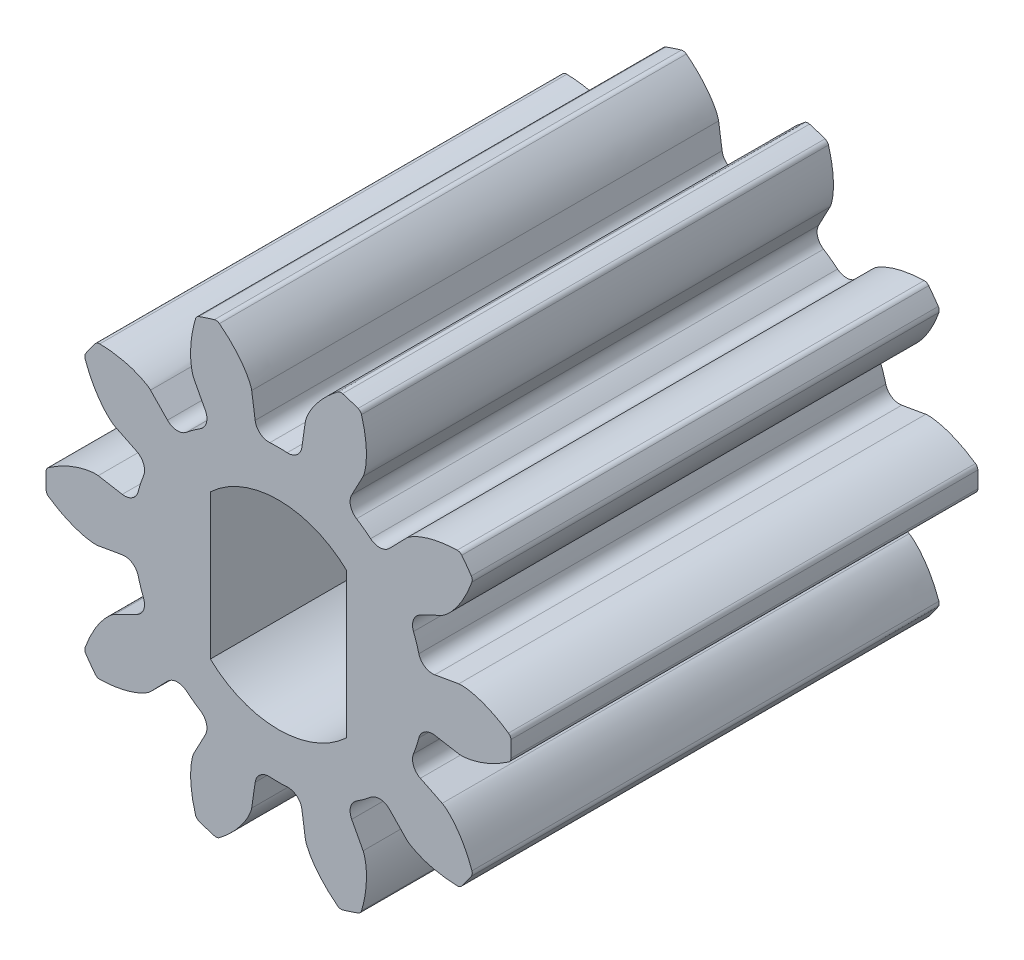
SolidWorks part; units mm, degrees
material "ABS"
ref_plane "Front" through (0, 0, 0) normal (0, 0, 1) x (1, 0, 0)
ref_plane "Top" through (0, 0, 0) normal (0, 1, 0) x (1, 0, 0)
ref_plane "Right" through (0, 0, 0) normal (1, 0, 0) x (0, 0, -1)
sketch "Sketch1" plane through (0, 0, 0) normal (0, 0, 1) x (1, 0, 0)
  circle A0 centre (0, 0) radius 6.35
extrude "Boss-Extrude1" add sketch "Sketch1" along normal blind 12.7
sketch "Sketch3" plane through (0, 0, 0) normal (0, 0, 1) x (1, 0, 0)
  line L0 (0, 0) -> (43.7181, 0) construction
  line L2 (0, 0) -> (-0.5624, 3.9287) construction
  line L3 (0, 0) -> (0.5624, 3.9287) construction
  line L4 (0.5624, 3.9287) -> (0.7046, 4.9224) construction
  line L5 (0, 0) -> (0, 61.276) construction
  line L6 (-0.5624, 3.9287) -> (-0.7046, 4.9224) construction
  circle A0 centre (0, 0) radius 6.35 construction
  circle A1 centre (0, 0) radius 5.2917 construction
  circle A2 centre (0, 0) radius 4.9725 construction
  arc A3 (0.5624, 3.9287) -> (-0.5624, 3.9287) centre (0, 0) ccw construction
  arc A5 (1.6642, 6.128) -> (-1.6642, 6.128) centre (0, 0) ccw
  spline S0 degree 4 poles (-0.7046, 4.9224) (-0.705, 4.9247) (-0.7061, 4.9311) (-0.7087, 4.9431) (-0.7137, 4.9626) (-0.721, 4.9872) (-0.7316, 5.0187) (-0.7454, 5.0554) (-0.7621, 5.0953) (-0.7818, 5.1381) (-0.8028, 5.1804) (-0.825, 5.2221) (-0.8483, 5.2631) (-0.8779, 5.3122) (-0.9151, 5.3703) (-0.9613, 5.437) (-1.0167, 5.511) (-1.0764, 5.5846) (-1.1378, 5.6556) (-1.2027, 5.7255) (-1.2676, 5.7919) (-1.338, 5.8588) (-1.4044, 5.9196) (-1.4819, 5.9855) (-1.5453, 6.0379) (-1.6323, 6.1046) (-1.6846, 6.1433) (-1.7469, 6.1876) (-1.7752, 6.2068) (-1.7925, 6.2186) knots 0 0 0 0 0 0.005377 0.015084 0.028532 0.04661 0.064855 0.092111 0.119476 0.146842 0.174209 0.201575 0.228941 0.256307 0.307035 0.361767 0.4165 0.471232 0.525964 0.580697 0.635429 0.690161 0.744894 0.799626 0.854358 0.909091 0.954545 1 1 1 1 1 construction
  spline S1 degree 4 poles (-0.7046, 4.9224) (-0.705, 4.9247) (-0.7061, 4.9311) (-0.7087, 4.9431) (-0.7137, 4.9626) (-0.721, 4.9872) (-0.7316, 5.0187) (-0.7454, 5.0554) (-0.7621, 5.0953) (-0.7818, 5.1381) (-0.8028, 5.1804) (-0.825, 5.2221) (-0.8483, 5.2631) (-0.8779, 5.3122) (-0.9151, 5.3703) (-0.9613, 5.437) (-1.0167, 5.511) (-1.0764, 5.5846) (-1.1378, 5.6556) (-1.2027, 5.7255) (-1.2676, 5.7919) (-1.338, 5.8588) (-1.4044, 5.9196) (-1.4819, 5.9855) (-1.5453, 6.0379) (-1.6134, 6.0902) (-1.647, 6.1153) (-1.6642, 6.128) knots 0 0 0 0 0 0.005377 0.015084 0.028532 0.04661 0.064855 0.092111 0.119476 0.146842 0.174209 0.201575 0.228941 0.256307 0.307035 0.361767 0.4165 0.471232 0.525964 0.580697 0.635429 0.690161 0.744894 0.799626 0.854358 0.909091 0.909091 0.909091 0.909091 0.909091
  spline S2 degree 4 poles (0.7046, 4.9224) (0.705, 4.9247) (0.7061, 4.9311) (0.7087, 4.9431) (0.7137, 4.9626) (0.721, 4.9872) (0.7316, 5.0187) (0.7454, 5.0554) (0.7621, 5.0953) (0.7818, 5.1381) (0.8028, 5.1804) (0.825, 5.2221) (0.8483, 5.2631) (0.8779, 5.3122) (0.9151, 5.3703) (0.9613, 5.437) (1.0167, 5.511) (1.0764, 5.5846) (1.1378, 5.6556) (1.2027, 5.7255) (1.2676, 5.7919) (1.338, 5.8588) (1.4044, 5.9196) (1.4819, 5.9855) (1.5453, 6.0379) (1.6323, 6.1046) (1.6846, 6.1433) (1.7469, 6.1876) (1.7752, 6.2068) (1.7925, 6.2186) knots 0 0 0 0 0 0.005377 0.015084 0.028532 0.04661 0.064855 0.092111 0.119476 0.146842 0.174209 0.201575 0.228941 0.256307 0.307035 0.361767 0.4165 0.471232 0.525964 0.580697 0.635429 0.690161 0.744894 0.799626 0.854358 0.909091 0.954545 1 1 1 1 1 construction
  spline S3 degree 4 poles (0.7046, 4.9224) (0.705, 4.9247) (0.7061, 4.9311) (0.7087, 4.9431) (0.7137, 4.9626) (0.721, 4.9872) (0.7316, 5.0187) (0.7454, 5.0554) (0.7621, 5.0953) (0.7818, 5.1381) (0.8028, 5.1804) (0.825, 5.2221) (0.8483, 5.2631) (0.8779, 5.3122) (0.9151, 5.3703) (0.9613, 5.437) (1.0167, 5.511) (1.0764, 5.5846) (1.1378, 5.6556) (1.2027, 5.7255) (1.2676, 5.7919) (1.338, 5.8588) (1.4044, 5.9196) (1.4819, 5.9855) (1.5453, 6.0379) (1.6134, 6.0902) (1.647, 6.1153) (1.6642, 6.128) knots 0 0 0 0 0 0.005377 0.015084 0.028532 0.04661 0.064855 0.092111 0.119476 0.146842 0.174209 0.201575 0.228941 0.256307 0.307035 0.361767 0.4165 0.471232 0.525964 0.580697 0.635429 0.690161 0.744894 0.799626 0.854358 0.909091 0.909091 0.909091 0.909091 0.909091
  point P0 (0, 3.9688)
sketch "DCLTBC" plane through (0, 0, 0) normal (0, 0, 1) x (1, 0, 0)
  line L0 (0, 0) -> (41.04, 0) construction
  line L1 (-0.5624, 3.9287) -> (-0.7046, 4.9224) construction
  line L2 (0.5624, 3.9287) -> (0.7046, 4.9224) construction
  line L3 (-0.5624, 3.9287) -> (-0.7046, 4.9224)
  line L4 (0.5624, 3.9287) -> (0.7046, 4.9224)
  line L5 (0, 0) -> (0, 104.9356) construction
  circle A0 centre (0, 0) radius 6.35
  circle A1 centre (0, 0) radius 5.2917 construction
  circle A2 centre (0, 0) radius 4.9725 construction
  arc A3 (0.5624, 3.9287) -> (-0.5624, 3.9287) centre (0, 0) ccw construction
  arc A4 (0.5624, 3.9287) -> (-0.5624, 3.9287) centre (0, 0) ccw
  spline S0 degree 4 poles (-988.7588, -149.038) (-11.8151, 2.4708) (-0.7866, 4.3496) (-0.6413, 4.6789) (-0.7137, 4.9626) (-0.721, 4.9872) (-0.7316, 5.0187) (-0.7454, 5.0554) (-0.7621, 5.0953) (-0.7818, 5.1381) (-0.8028, 5.1804) (-0.825, 5.2221) (-0.8483, 5.2631) (-0.8779, 5.3122) (-0.9151, 5.3703) (-0.9613, 5.437) (-1.0167, 5.511) (-1.0764, 5.5846) (-1.1378, 5.6556) (-1.2027, 5.7255) (-1.2676, 5.7919) (-1.338, 5.8588) (-1.4044, 5.9196) (-1.4819, 5.9855) (-1.8387, 6.2805) (-3.231, 7.2231) (17.05, -7.85) (-807.2758, 598.5552) knots -0.632257 -0.632257 -0.632257 -0.632257 -0.632257 0.005377 0.015084 0.028532 0.04661 0.064855 0.092111 0.119476 0.146842 0.174209 0.201575 0.228941 0.256307 0.307035 0.361767 0.4165 0.471232 0.525964 0.580697 0.635429 0.690161 0.744894 0.799626 0.854358 1.920904 1.920904 1.920904 1.920904 1.920904 only from (-0.7046, 4.9224) to (-1.6642, 6.128) construction
  spline S1 degree 4 poles (988.7588, -149.038) (11.8151, 2.4708) (0.7866, 4.3496) (0.6413, 4.6789) (0.7137, 4.9626) (0.721, 4.9872) (0.7316, 5.0187) (0.7454, 5.0554) (0.7621, 5.0953) (0.7818, 5.1381) (0.8028, 5.1804) (0.825, 5.2221) (0.8483, 5.2631) (0.8779, 5.3122) (0.9151, 5.3703) (0.9613, 5.437) (1.0167, 5.511) (1.0764, 5.5846) (1.1378, 5.6556) (1.2027, 5.7255) (1.2676, 5.7919) (1.338, 5.8588) (1.4044, 5.9196) (1.4819, 5.9855) (1.8387, 6.2805) (3.231, 7.2231) (-17.05, -7.85) (807.2758, 598.5552) knots -0.632257 -0.632257 -0.632257 -0.632257 -0.632257 0.005377 0.015084 0.028532 0.04661 0.064855 0.092111 0.119476 0.146842 0.174209 0.201575 0.228941 0.256307 0.307035 0.361767 0.4165 0.471232 0.525964 0.580697 0.635429 0.690161 0.744894 0.799626 0.854358 1.920904 1.920904 1.920904 1.920904 1.920904 only from (0.7046, 4.9224) to (1.6642, 6.128) construction
  spline S2 degree 4 poles (-0.7046, 4.9224) (-0.705, 4.9247) (-0.7061, 4.9311) (-0.7087, 4.9431) (-0.7137, 4.9626) (-0.721, 4.9872) (-0.7316, 5.0187) (-0.7454, 5.0554) (-0.7621, 5.0953) (-0.7818, 5.1381) (-0.8028, 5.1804) (-0.825, 5.2221) (-0.8483, 5.2631) (-0.8779, 5.3122) (-0.9151, 5.3703) (-0.9613, 5.437) (-1.0167, 5.511) (-1.0764, 5.5846) (-1.1378, 5.6556) (-1.2027, 5.7255) (-1.2676, 5.7919) (-1.338, 5.8588) (-1.4044, 5.9196) (-1.4819, 5.9855) (-1.5453, 6.0379) (-1.6134, 6.0902) (-1.647, 6.1153) (-1.6642, 6.128) knots 0 0 0 0 0 0.005377 0.015084 0.028532 0.04661 0.064855 0.092111 0.119476 0.146842 0.174209 0.201575 0.228941 0.256307 0.307035 0.361767 0.4165 0.471232 0.525964 0.580697 0.635429 0.690161 0.744894 0.799626 0.854358 0.909091 0.909091 0.909091 0.909091 0.909091
  spline S3 degree 4 poles (0.7046, 4.9224) (0.705, 4.9247) (0.7061, 4.9311) (0.7087, 4.9431) (0.7137, 4.9626) (0.721, 4.9872) (0.7316, 5.0187) (0.7454, 5.0554) (0.7621, 5.0953) (0.7818, 5.1381) (0.8028, 5.1804) (0.825, 5.2221) (0.8483, 5.2631) (0.8779, 5.3122) (0.9151, 5.3703) (0.9613, 5.437) (1.0167, 5.511) (1.0764, 5.5846) (1.1378, 5.6556) (1.2027, 5.7255) (1.2676, 5.7919) (1.338, 5.8588) (1.4044, 5.9196) (1.4819, 5.9855) (1.5453, 6.0379) (1.6134, 6.0902) (1.647, 6.1153) (1.6642, 6.128) knots 0 0 0 0 0 0.005377 0.015084 0.028532 0.04661 0.064855 0.092111 0.119476 0.146842 0.174209 0.201575 0.228941 0.256307 0.307035 0.361767 0.4165 0.471232 0.525964 0.580697 0.635429 0.690161 0.744894 0.799626 0.854358 0.909091 0.909091 0.909091 0.909091 0.909091
extrude "Cut-Extrude-DCLTBC" cut sketch "DCLTBC" along normal through all
fillet "Fillet-Tip-DCLTBC" radius 0.1775 2 edges at (1.6642, 6.128, 6.35) (-1.6642, 6.128, 6.35)
fillet "Fillet-Root-DCLTBC" radius 0.3551 2 edges at (-0.5624, 3.9287, 6.35) (0.5624, 3.9287, 6.35)
pattern_circular "CirPattern-DCLTBC" count 10 over 360 about axis through (0, 0, 12.7) along (0, 0, 1) of "Cut-Extrude-DCLTBC", "Fillet-Tip-DCLTBC", "Fillet-Root-DCLTBC"
sketch "DCGTBC" [suppressed] plane through (0, 0, 0) normal (0, 0, 1) x (1, 0, 0)
  line L0 (0, 0) -> (41.04, 0) construction
  line L1 (-22.6634, 1.9828) -> (0, 0) construction
  line L2 (0, 0) -> (22.6634, 1.9828) construction
  line L3 (0, 0) -> (-16.5124, 0)
  line L5 (0, 0) -> (0, 104.9356) construction
  circle A0 centre (0, 0) radius 25
  circle A1 centre (0, 0) radius 24 construction
  circle A2 centre (0, 0) radius 21.7514 construction
  arc A3 (0.0626, 22.7499) -> (-0.0626, 22.7499) centre (0, 0) ccw construction
  arc A11 (22.6634, 1.9828) -> (-22.6634, 1.9828) centre (0, 0) ccw
  spline S4 degree 4 poles (999.7589, -2.0808) (12.8658, 20.0937) (0.2547, 20.6746) (0.0189, 21.2606) (0.0654, 21.8429) (0.0715, 21.8997) (0.0812, 21.973) (0.095, 22.0592) (0.1126, 22.1539) (0.1343, 22.2566) (0.1583, 22.3589) (0.1845, 22.4607) (0.2124, 22.562) (0.2486, 22.6844) (0.2952, 22.8308) (0.3543, 23.0013) (0.4268, 23.1939) (0.5065, 23.3893) (0.5897, 23.5809) (0.6793, 23.7735) (0.7698, 23.9592) (0.8695, 24.151) (0.9643, 24.3275) (1.0767, 24.524) (1.517, 25.277) (3.0654, 27.5692) (-13.787, 0.9944) (540.7091, 867.0187) knots -0.561807 -0.561807 -0.561807 -0.561807 -0.561807 0.005377 0.015084 0.028532 0.04661 0.064855 0.092111 0.119476 0.146842 0.174209 0.201575 0.228941 0.256307 0.307035 0.361767 0.4165 0.471232 0.525964 0.580697 0.635429 0.690161 0.744894 0.799626 0.854358 1.731906 1.731906 1.731906 1.731906 1.731906 only from (0.0598, 21.7513) to (1.3455, 24.9638) construction
  spline S5 degree 4 poles (-999.7589, -2.0808) (-12.8658, 20.0937) (-0.2547, 20.6746) (-0.0189, 21.2606) (-0.0654, 21.8429) (-0.0715, 21.8997) (-0.0812, 21.973) (-0.095, 22.0592) (-0.1126, 22.1539) (-0.1343, 22.2566) (-0.1583, 22.3589) (-0.1845, 22.4607) (-0.2124, 22.562) (-0.2486, 22.6844) (-0.2952, 22.8308) (-0.3543, 23.0013) (-0.4268, 23.1939) (-0.5065, 23.3893) (-0.5897, 23.5809) (-0.6793, 23.7735) (-0.7698, 23.9592) (-0.8695, 24.151) (-0.9643, 24.3275) (-1.0767, 24.524) (-1.517, 25.277) (-3.0654, 27.5692) (13.787, 0.9944) (-540.7091, 867.0187) knots -0.561807 -0.561807 -0.561807 -0.561807 -0.561807 0.005377 0.015084 0.028532 0.04661 0.064855 0.092111 0.119476 0.146842 0.174209 0.201575 0.228941 0.256307 0.307035 0.361767 0.4165 0.471232 0.525964 0.580697 0.635429 0.690161 0.744894 0.799626 0.854358 1.731906 1.731906 1.731906 1.731906 1.731906 only from (-0.0598, 21.7513) to (-1.3455, 24.9638) construction
  spline S6 degree 4 poles (0.0598, 21.7513) (0.0599, 21.7565) (0.0603, 21.7709) (0.0618, 21.7983) (0.0654, 21.8429) (0.0715, 21.8997) (0.0812, 21.973) (0.095, 22.0592) (0.1126, 22.1539) (0.1343, 22.2566) (0.1583, 22.3589) (0.1845, 22.4607) (0.2124, 22.562) (0.2486, 22.6844) (0.2952, 22.8308) (0.3543, 23.0013) (0.4268, 23.1939) (0.5065, 23.3893) (0.5897, 23.5809) (0.6793, 23.7735) (0.7698, 23.9592) (0.8695, 24.151) (0.9643, 24.3275) (1.0767, 24.524) (1.1693, 24.6823) (1.27, 24.8447) (1.3197, 24.9235) (1.3455, 24.9638) knots 0 0 0 0 0 0.005377 0.015084 0.028532 0.04661 0.064855 0.092111 0.119476 0.146842 0.174209 0.201575 0.228941 0.256307 0.307035 0.361767 0.4165 0.471232 0.525964 0.580697 0.635429 0.690161 0.744894 0.799626 0.854358 0.909091 0.909091 0.909091 0.909091 0.909091
  spline S7 degree 4 poles (-0.0598, 21.7513) (-0.0599, 21.7565) (-0.0603, 21.7709) (-0.0618, 21.7983) (-0.0654, 21.8429) (-0.0715, 21.8997) (-0.0812, 21.973) (-0.095, 22.0592) (-0.1126, 22.1539) (-0.1343, 22.2566) (-0.1583, 22.3589) (-0.1845, 22.4607) (-0.2124, 22.562) (-0.2486, 22.6844) (-0.2952, 22.8308) (-0.3543, 23.0013) (-0.4268, 23.1939) (-0.5065, 23.3893) (-0.5897, 23.5809) (-0.6793, 23.7735) (-0.7698, 23.9592) (-0.8695, 24.151) (-0.9643, 24.3275) (-1.0767, 24.524) (-1.1693, 24.6823) (-1.27, 24.8447) (-1.3197, 24.9235) (-1.3455, 24.9638) knots 0 0 0 0 0 0.005377 0.015084 0.028532 0.04661 0.064855 0.092111 0.119476 0.146842 0.174209 0.201575 0.228941 0.256307 0.307035 0.361767 0.4165 0.471232 0.525964 0.580697 0.635429 0.690161 0.744894 0.799626 0.854358 0.909091 0.909091 0.909091 0.909091 0.909091
  dimension "D1" = 5
  dimension "D2" = 5
extrude "Cut-Extrude-DCGTBC" [suppressed] cut sketch "DCGTBC" along normal through all
fillet "Fillet-Tip-DCGTBC" [suppressed] radius 0.1775
pattern_circular "CirPattern-DCGTBC" [suppressed] count 10 over 360
sketch "Sketch4" plane through (0, 0, 12.7) normal (0, 0, 1) x (1, 0, 0)
  circle A1 centre (0, 0) radius 2.7051
  dimension "D1" = 5.4102
extrude "Cut-Extrude2" cut sketch "Sketch4" against normal through all
sketch "Sketch5" plane through (0, 0, 12.7) normal (0, 0, 1) x (1, 0, 0)
  line L0 (-1.8542, 1.9696) -> (-1.8542, -1.9696)
  line L1 (1.8542, 1.9696) -> (1.8542, -1.9696)
  circle A0 centre (0, 0) radius 2.7051 construction
  circle A1 centre (0, 0) radius 2.7051
  dimension "D1" = 3.7084
extrude "Boss-Extrude2" add sketch "Sketch5" against normal through all contours L0 A1 | L1 A1
sketch "Sketch6" plane through (0, 0, 0) normal (0, 0, -1) x (-1, 0, 0)
  line L4 (-1.9655, 2.0878) -> (-1.9655, -2.0878)
  line L5 (1.9655, -2.0878) -> (1.9655, 2.0878)
  arc A4 (-1.9655, -2.0878) -> (1.9655, -2.0878) centre (0, 0) ccw
  arc A5 (1.9655, 2.0878) -> (-1.9655, 2.0878) centre (0, 0) ccw
extrude "Boss-Extrude3" add sketch "Sketch6" against normal blind 3.175
sketch "Sketch8" plane through (0, 0, 12.7) normal (0, 0, 1) x (1, 0, 0)
  line L50 (0.7297, 4.9185) -> (0.6357, 4.2621)
  line L51 (-0.6357, 4.2621) -> (-0.7297, 4.9185)
  line L52 (-2.3007, 4.4081) -> (-1.9909, 3.8218)
  line L53 (-3.0196, 3.0745) -> (-3.4814, 3.5503)
  line L54 (-4.4523, 2.2139) -> (-3.8571, 1.9217)
  line L55 (-4.25, 0.7124) -> (-4.9033, 0.8259)
  line L56 (-4.9033, -0.8259) -> (-4.25, -0.7124)
  line L57 (-3.8571, -1.9217) -> (-4.4523, -2.2139)
  line L58 (-3.4814, -3.5503) -> (-3.0196, -3.0745)
  line L59 (-1.9909, -3.8218) -> (-2.3007, -4.4081)
  line L60 (-0.7297, -4.9185) -> (-0.6357, -4.2621)
  line L61 (0.6357, -4.2621) -> (0.7297, -4.9185)
  line L62 (2.3007, -4.4081) -> (1.9909, -3.8218)
  line L63 (3.0196, -3.0745) -> (3.4814, -3.5503)
  line L64 (4.4523, -2.2139) -> (3.8571, -1.9217)
  line L65 (4.25, -0.7124) -> (4.9033, -0.8259)
  line L66 (4.9033, 0.8259) -> (4.25, 0.7124)
  line L67 (3.8571, 1.9217) -> (4.4523, 2.2139)
  line L68 (3.4814, 3.5503) -> (3.0196, 3.0745)
  line L69 (1.9909, 3.8218) -> (2.3007, 4.4081)
  line L74 (0.7297, 4.9185) -> (0.6357, 4.2621)
  line L75 (-0.6357, 4.2621) -> (-0.7297, 4.9185)
  line L76 (-2.3007, 4.4081) -> (-1.9909, 3.8218)
  line L77 (-3.0196, 3.0745) -> (-3.4814, 3.5503)
  line L78 (-4.4523, 2.2139) -> (-3.8571, 1.9217)
  line L79 (-4.25, 0.7124) -> (-4.9033, 0.8259)
  line L80 (-4.9033, -0.8259) -> (-4.25, -0.7124)
  line L81 (-3.8571, -1.9217) -> (-4.4523, -2.2139)
  line L82 (-3.4814, -3.5503) -> (-3.0196, -3.0745)
  line L83 (-1.9909, -3.8218) -> (-2.3007, -4.4081)
  line L84 (-0.7297, -4.9185) -> (-0.6357, -4.2621)
  line L85 (0.6357, -4.2621) -> (0.7297, -4.9185)
  line L86 (2.3007, -4.4081) -> (1.9909, -3.8218)
  line L87 (3.0196, -3.0745) -> (3.4814, -3.5503)
  line L88 (4.4523, -2.2139) -> (3.8571, -1.9217)
  line L89 (4.25, -0.7124) -> (4.9033, -0.8259)
  line L90 (4.9033, 0.8259) -> (4.25, 0.7124)
  line L91 (3.8571, 1.9217) -> (4.4523, 2.2139)
  line L92 (3.4814, 3.5503) -> (3.0196, 3.0745)
  line L93 (1.9909, 3.8218) -> (2.3007, 4.4081)
  arc A150 (2.1634, 5.9431) -> (1.743, 6.0797) centre (0, 0) ccw
  arc A151 (1.743, 6.0797) -> (1.6082, 6.054) centre (1.7011, 5.9334) ccw
  arc A152 (0.2363, 3.9363) -> (0.6357, 4.2621) centre (0.2591, 4.3161) ccw
  arc A153 (0.2363, 3.9363) -> (-0.2363, 3.9363) centre (0, 0) ccw
  arc A154 (-0.6357, 4.2621) -> (-0.2363, 3.9363) centre (-0.2591, 4.3161) ccw
  arc A155 (-1.6082, 6.054) -> (-1.743, 6.0797) centre (-1.7011, 5.9334) ccw
  arc A156 (-1.743, 6.0797) -> (-2.1634, 5.9431) centre (0, 0) ccw
  arc A157 (-2.1634, 5.9431) -> (-2.2573, 5.8431) centre (-2.1114, 5.8001) ccw
  arc A158 (-2.1225, 3.3234) -> (-1.9909, 3.8218) centre (-2.3273, 3.6441) ccw
  arc A159 (-2.1225, 3.3234) -> (-2.5049, 3.0456) centre (0, 0) ccw
  arc A160 (-3.0196, 3.0745) -> (-2.5049, 3.0456) centre (-2.7465, 3.3395) ccw
  arc A161 (-4.8595, 3.9525) -> (-4.9837, 3.894) centre (-4.8638, 3.8004) ccw
  arc A162 (-4.9837, 3.894) -> (-5.2435, 3.5364) centre (0, 0) ccw
  arc A163 (-5.2435, 3.5364) -> (-5.2607, 3.4003) centre (-5.1174, 3.4514) ccw
  arc A164 (-3.6706, 1.4411) -> (-3.8571, 1.9217) centre (-4.0247, 1.5802) ccw
  arc A165 (-3.6706, 1.4411) -> (-3.8166, 0.9916) centre (0, 0) ccw
  arc A166 (-4.25, 0.7124) -> (-3.8166, 0.9916) centre (-4.1849, 1.0873) ccw
  arc A167 (-6.2546, 0.3412) -> (-6.3207, 0.221) centre (-6.1687, 0.2157) ccw
  arc A168 (-6.3207, 0.221) -> (-6.3207, -0.221) centre (0, 0) ccw
  arc A169 (-6.3207, -0.221) -> (-6.2546, -0.3412) centre (-6.1687, -0.2157) ccw
  arc A170 (-3.8166, -0.9916) -> (-4.25, -0.7124) centre (-4.1849, -1.0873) ccw
  arc A171 (-3.8166, -0.9916) -> (-3.6706, -1.4411) centre (0, 0) ccw
  arc A172 (-3.8571, -1.9217) -> (-3.6706, -1.4411) centre (-4.0247, -1.5802) ccw
  arc A173 (-5.2607, -3.4003) -> (-5.2435, -3.5364) centre (-5.1174, -3.4514) ccw
  arc A174 (-5.2435, -3.5364) -> (-4.9837, -3.894) centre (0, 0) ccw
  arc A175 (-4.9837, -3.894) -> (-4.8595, -3.9525) centre (-4.8638, -3.8004) ccw
  arc A176 (-2.5049, -3.0456) -> (-3.0196, -3.0745) centre (-2.7465, -3.3395) ccw
  arc A177 (-2.5049, -3.0456) -> (-2.1225, -3.3234) centre (0, 0) ccw
  arc A178 (-1.9909, -3.8218) -> (-2.1225, -3.3234) centre (-2.3273, -3.6441) ccw
  arc A179 (-2.2573, -5.8431) -> (-2.1634, -5.9431) centre (-2.1114, -5.8001) ccw
  arc A180 (-2.1634, -5.9431) -> (-1.743, -6.0797) centre (0, 0) ccw
  arc A181 (-1.743, -6.0797) -> (-1.6082, -6.054) centre (-1.7011, -5.9334) ccw
  arc A182 (-0.2363, -3.9363) -> (-0.6357, -4.2621) centre (-0.2591, -4.3161) ccw
  arc A183 (-0.2363, -3.9363) -> (0.2363, -3.9363) centre (0, 0) ccw
  arc A184 (0.6357, -4.2621) -> (0.2363, -3.9363) centre (0.2591, -4.3161) ccw
  arc A185 (1.6082, -6.054) -> (1.743, -6.0797) centre (1.7011, -5.9334) ccw
  arc A186 (1.743, -6.0797) -> (2.1634, -5.9431) centre (0, 0) ccw
  arc A187 (2.1634, -5.9431) -> (2.2573, -5.8431) centre (2.1114, -5.8001) ccw
  arc A188 (2.1225, -3.3234) -> (1.9909, -3.8218) centre (2.3273, -3.6441) ccw
  arc A189 (2.1225, -3.3234) -> (2.5049, -3.0456) centre (0, 0) ccw
  arc A190 (3.0196, -3.0745) -> (2.5049, -3.0456) centre (2.7465, -3.3395) ccw
  arc A191 (4.8595, -3.9525) -> (4.9837, -3.894) centre (4.8638, -3.8004) ccw
  arc A192 (4.9837, -3.894) -> (5.2435, -3.5364) centre (0, 0) ccw
  arc A193 (5.2435, -3.5364) -> (5.2607, -3.4003) centre (5.1174, -3.4514) ccw
  arc A194 (3.6706, -1.4411) -> (3.8571, -1.9217) centre (4.0247, -1.5802) ccw
  arc A195 (3.6706, -1.4411) -> (3.8166, -0.9916) centre (0, 0) ccw
  arc A196 (4.25, -0.7124) -> (3.8166, -0.9916) centre (4.1849, -1.0873) ccw
  arc A197 (6.2546, -0.3412) -> (6.3207, -0.221) centre (6.1687, -0.2157) ccw
  arc A198 (6.3207, -0.221) -> (6.3207, 0.221) centre (0, 0) ccw
  arc A199 (6.3207, 0.221) -> (6.2546, 0.3412) centre (6.1687, 0.2157) ccw
  arc A200 (3.8166, 0.9916) -> (4.25, 0.7124) centre (4.1849, 1.0873) ccw
  arc A201 (3.8166, 0.9916) -> (3.6706, 1.4411) centre (0, 0) ccw
  arc A202 (3.8571, 1.9217) -> (3.6706, 1.4411) centre (4.0247, 1.5802) ccw
  arc A203 (5.2607, 3.4003) -> (5.2435, 3.5364) centre (5.1174, 3.4514) ccw
  arc A204 (5.2435, 3.5364) -> (4.9837, 3.894) centre (0, 0) ccw
  arc A205 (4.9837, 3.894) -> (4.8595, 3.9525) centre (4.8638, 3.8004) ccw
  arc A206 (2.5049, 3.0456) -> (3.0196, 3.0745) centre (2.7465, 3.3395) ccw
  arc A207 (2.5049, 3.0456) -> (2.1225, 3.3234) centre (0, 0) ccw
  arc A208 (1.9909, 3.8218) -> (2.1225, 3.3234) centre (2.3273, 3.6441) ccw
  arc A209 (2.2573, 5.8431) -> (2.1634, 5.9431) centre (2.1114, 5.8001) ccw
  arc A222 (2.1634, 5.9431) -> (1.743, 6.0797) centre (0, 0) ccw
  arc A223 (1.743, 6.0797) -> (1.6082, 6.054) centre (1.7011, 5.9334) ccw
  arc A224 (0.2363, 3.9363) -> (0.6357, 4.2621) centre (0.2591, 4.3161) ccw
  arc A225 (0.2363, 3.9363) -> (-0.2363, 3.9363) centre (0, 0) ccw
  arc A226 (-0.6357, 4.2621) -> (-0.2363, 3.9363) centre (-0.2591, 4.3161) ccw
  arc A227 (-1.6082, 6.054) -> (-1.743, 6.0797) centre (-1.7011, 5.9334) ccw
  arc A228 (-1.743, 6.0797) -> (-2.1634, 5.9431) centre (0, 0) ccw
  arc A229 (-2.1634, 5.9431) -> (-2.2573, 5.8431) centre (-2.1114, 5.8001) ccw
  arc A230 (-2.1225, 3.3234) -> (-1.9909, 3.8218) centre (-2.3273, 3.6441) ccw
  arc A231 (-2.1225, 3.3234) -> (-2.5049, 3.0456) centre (0, 0) ccw
  arc A232 (-3.0196, 3.0745) -> (-2.5049, 3.0456) centre (-2.7465, 3.3395) ccw
  arc A233 (-4.8595, 3.9525) -> (-4.9837, 3.894) centre (-4.8638, 3.8004) ccw
  arc A234 (-4.9837, 3.894) -> (-5.2435, 3.5364) centre (0, 0) ccw
  arc A235 (-5.2435, 3.5364) -> (-5.2607, 3.4003) centre (-5.1174, 3.4514) ccw
  arc A236 (-3.6706, 1.4411) -> (-3.8571, 1.9217) centre (-4.0247, 1.5802) ccw
  arc A237 (-3.6706, 1.4411) -> (-3.8166, 0.9916) centre (0, 0) ccw
  arc A238 (-4.25, 0.7124) -> (-3.8166, 0.9916) centre (-4.1849, 1.0873) ccw
  arc A239 (-6.2546, 0.3412) -> (-6.3207, 0.221) centre (-6.1687, 0.2157) ccw
  arc A240 (-6.3207, 0.221) -> (-6.3207, -0.221) centre (0, 0) ccw
  arc A241 (-6.3207, -0.221) -> (-6.2546, -0.3412) centre (-6.1687, -0.2157) ccw
  arc A242 (-3.8166, -0.9916) -> (-4.25, -0.7124) centre (-4.1849, -1.0873) ccw
  arc A243 (-3.8166, -0.9916) -> (-3.6706, -1.4411) centre (0, 0) ccw
  arc A244 (-3.8571, -1.9217) -> (-3.6706, -1.4411) centre (-4.0247, -1.5802) ccw
  arc A245 (-5.2607, -3.4003) -> (-5.2435, -3.5364) centre (-5.1174, -3.4514) ccw
  arc A246 (-5.2435, -3.5364) -> (-4.9837, -3.894) centre (0, 0) ccw
  arc A247 (-4.9837, -3.894) -> (-4.8595, -3.9525) centre (-4.8638, -3.8004) ccw
  arc A248 (-2.5049, -3.0456) -> (-3.0196, -3.0745) centre (-2.7465, -3.3395) ccw
  arc A249 (-2.5049, -3.0456) -> (-2.1225, -3.3234) centre (0, 0) ccw
  arc A250 (-1.9909, -3.8218) -> (-2.1225, -3.3234) centre (-2.3273, -3.6441) ccw
  arc A251 (-2.2573, -5.8431) -> (-2.1634, -5.9431) centre (-2.1114, -5.8001) ccw
  arc A252 (-2.1634, -5.9431) -> (-1.743, -6.0797) centre (0, 0) ccw
  arc A253 (-1.743, -6.0797) -> (-1.6082, -6.054) centre (-1.7011, -5.9334) ccw
  arc A254 (-0.2363, -3.9363) -> (-0.6357, -4.2621) centre (-0.2591, -4.3161) ccw
  arc A255 (-0.2363, -3.9363) -> (0.2363, -3.9363) centre (0, 0) ccw
  arc A256 (0.6357, -4.2621) -> (0.2363, -3.9363) centre (0.2591, -4.3161) ccw
  arc A257 (1.6082, -6.054) -> (1.743, -6.0797) centre (1.7011, -5.9334) ccw
  arc A258 (1.743, -6.0797) -> (2.1634, -5.9431) centre (0, 0) ccw
  arc A259 (2.1634, -5.9431) -> (2.2573, -5.8431) centre (2.1114, -5.8001) ccw
  arc A260 (2.1225, -3.3234) -> (1.9909, -3.8218) centre (2.3273, -3.6441) ccw
  arc A261 (2.1225, -3.3234) -> (2.5049, -3.0456) centre (0, 0) ccw
  arc A262 (3.0196, -3.0745) -> (2.5049, -3.0456) centre (2.7465, -3.3395) ccw
  arc A263 (4.8595, -3.9525) -> (4.9837, -3.894) centre (4.8638, -3.8004) ccw
  arc A264 (4.9837, -3.894) -> (5.2435, -3.5364) centre (0, 0) ccw
  arc A265 (5.2435, -3.5364) -> (5.2607, -3.4003) centre (5.1174, -3.4514) ccw
  arc A266 (3.6706, -1.4411) -> (3.8571, -1.9217) centre (4.0247, -1.5802) ccw
  arc A267 (3.6706, -1.4411) -> (3.8166, -0.9916) centre (0, 0) ccw
  arc A268 (4.25, -0.7124) -> (3.8166, -0.9916) centre (4.1849, -1.0873) ccw
  arc A269 (6.2546, -0.3412) -> (6.3207, -0.221) centre (6.1687, -0.2157) ccw
  arc A270 (6.3207, -0.221) -> (6.3207, 0.221) centre (0, 0) ccw
  arc A271 (6.3207, 0.221) -> (6.2546, 0.3412) centre (6.1687, 0.2157) ccw
  arc A272 (3.8166, 0.9916) -> (4.25, 0.7124) centre (4.1849, 1.0873) ccw
  arc A273 (3.8166, 0.9916) -> (3.6706, 1.4411) centre (0, 0) ccw
  arc A274 (3.8571, 1.9217) -> (3.6706, 1.4411) centre (4.0247, 1.5802) ccw
  arc A275 (5.2607, 3.4003) -> (5.2435, 3.5364) centre (5.1174, 3.4514) ccw
  arc A276 (5.2435, 3.5364) -> (4.9837, 3.894) centre (0, 0) ccw
  arc A277 (4.9837, 3.894) -> (4.8595, 3.9525) centre (4.8638, 3.8004) ccw
  arc A278 (2.5049, 3.0456) -> (3.0196, 3.0745) centre (2.7465, 3.3395) ccw
  arc A279 (2.5049, 3.0456) -> (2.1225, 3.3234) centre (0, 0) ccw
  arc A280 (1.9909, 3.8218) -> (2.1225, 3.3234) centre (2.3273, 3.6441) ccw
  arc A281 (2.2573, 5.8431) -> (2.1634, 5.9431) centre (2.1114, 5.8001) ccw
  spline S50 degree 3 poles (-2981.1226, 322.9869) (138.6336, -64.8997) (11.7316, 18.4787) (1.005, 5.4571) (0.9336, 5.3577) (0.8415, 5.2008) (0.8133, 5.1471) (0.7762, 5.0638) (0.7647, 5.0354) (-0.1197, 2.5272) (1.8075, -0.8005) (2869.2547, -871.9201) knots -33.999078 -33.999078 -33.999078 -33.999078 0.5 0.5 0.75 0.75 0.875 0.875 0.9375 0.9375 6.320462 6.320462 6.320462 6.320462 only from (1.6082, 6.054) to (0.7297, 4.9185)
  spline S51 degree 3 poles (-2814.1262, -1035.4767) (-1.5149, -0.8224) (0.1127, 2.55) (-0.7648, 5.0357) (-0.7763, 5.0639) (-0.8136, 5.1477) (-0.8422, 5.202) (-0.9344, 5.359) (-1.005, 5.4571) (-11.3131, 17.9741) (-133.6801, -53.9624) (2992.326, -173.0623) knots -5.275059 -5.275059 -5.275059 -5.275059 0.0625 0.0625 0.125 0.125 0.25 0.25 0.5 0.5 33.744281 33.744281 33.744281 33.744281 only from (-0.7297, 4.9185) to (-1.6082, 6.054)
  spline S52 degree 3 poles (-2601.6258, -1490.958) (150.3041, 28.9818) (-1.3704, 21.8453) (-2.3945, 5.0056) (-2.3939, 4.8833) (-2.3761, 4.7021) (-2.3674, 4.6421) (-2.3484, 4.5529) (-2.3411, 4.5232) (-1.5823, 1.9742) (1.9329, 0.4148) (2833.7776, 981.1074) knots -33.999078 -33.999078 -33.999078 -33.999078 0.5 0.5 0.75 0.75 0.875 0.875 0.9375 0.9375 6.320462 6.320462 6.320462 6.320462 only from (-2.2573, 5.8431) to (-2.3007, 4.4081)
  spline S53 degree 3 poles (-1668.038, -2491.8202) (-0.7422, -1.5558) (-1.4076, 2.1292) (-3.5786, 3.6244) (-3.6045, 3.6405) (-3.684, 3.6864) (-3.739, 3.7135) (-3.9059, 3.7863) (-4.0207, 3.8242) (-19.7174, 7.8917) (-76.4312, -122.2317) (2522.566, 1618.8348) knots -5.275059 -5.275059 -5.275059 -5.275059 0.0625 0.0625 0.125 0.125 0.25 0.25 0.5 0.5 33.744281 33.744281 33.744281 33.744281 only from (-3.4814, 3.5503) to (-4.8595, 3.9525)
  spline S54 degree 3 poles (-1228.3963, -2735.4076) (104.5635, 111.7933) (-13.949, 16.8677) (-4.8795, 2.6422) (-4.807, 2.5435) (-4.6862, 2.4075) (-4.6439, 2.364) (-4.5761, 2.303) (-4.5526, 2.2833) (-2.4405, 0.6671) (1.3199, 1.4717) (1715.8938, 2459.3853) knots -33.999078 -33.999078 -33.999078 -33.999078 0.5 0.5 0.75 0.75 0.875 0.875 0.9375 0.9375 6.320462 6.320462 6.320462 6.320462 only from (-5.2607, 3.4003) to (-4.4523, 2.2139)
  spline S55 degree 3 poles (115.1841, -2996.373) (0.314, -1.6949) (-2.3903, 0.8952) (-5.0255, 0.8287) (-5.056, 0.8266) (-5.1472, 0.817) (-5.2077, 0.8065) (-5.3855, 0.7673) (-5.5006, 0.7305) (-20.5904, -5.2051) (10.0118, -143.8127) (1089.2716, 2792.3919) knots -5.275059 -5.275059 -5.275059 -5.275059 0.0625 0.0625 0.125 0.125 0.25 0.25 0.5 0.5 33.744281 33.744281 33.744281 33.744281 only from (-4.9033, 0.8259) to (-6.2546, 0.3412)
  spline S56 degree 3 poles (614.0388, -2935.0245) (18.8832, 151.9035) (-21.1996, 5.4472) (-5.5006, -0.7305) (-5.384, -0.7677) (-5.2063, -0.8068) (-5.1465, -0.8171) (-5.0558, -0.8266) (-5.0253, -0.8288) (-2.3666, -0.8948) (0.2028, 1.9664) (-57.4032, 2998.2615) knots -33.999078 -33.999078 -33.999078 -33.999078 0.5 0.5 0.75 0.75 0.875 0.875 0.9375 0.9375 6.320462 6.320462 6.320462 6.320462 only from (-6.2546, -0.3412) to (-4.9033, -0.8259)
  spline S57 degree 3 poles (1854.4097, -2356.4131) (1.2503, -1.1867) (-2.46, -0.6808) (-4.5529, -2.2835) (-4.5762, -2.3031) (-4.6444, -2.3645) (-4.6872, -2.4085) (-4.808, -2.5447) (-4.8794, -2.6421) (-13.5985, -16.3137) (92.6307, -110.4621) (-760.0876, 2899.3503) knots -5.275059 -5.275059 -5.275059 -5.275059 0.0625 0.0625 0.125 0.125 0.25 0.25 0.5 0.5 33.744281 33.744281 33.744281 33.744281 only from (-4.4523, -2.2139) to (-5.2607, -3.4003)
  spline S58 degree 3 poles (2221.9319, -2013.5618) (-74.0099, 133.9918) (-20.3526, -8.0539) (-4.0207, -3.8242) (-3.9045, -3.7858) (-3.7377, -3.7129) (-3.6834, -3.6861) (-3.6044, -3.6404) (-3.5784, -3.6242) (-1.3886, -2.1149) (-0.9918, 1.7101) (-1808.774, 2391.9038) knots -33.999078 -33.999078 -33.999078 -33.999078 0.5 0.5 0.75 0.75 0.875 0.875 0.9375 0.9375 6.320462 6.320462 6.320462 6.320462 only from (-4.8595, -3.9525) to (-3.4814, -3.5503)
  spline S59 degree 3 poles (2885.3139, -816.3836) (1.709, -0.2252) (-1.59, -1.9967) (-2.3412, -4.5235) (-2.3485, -4.5531) (-2.3676, -4.6428) (-2.3763, -4.7036) (-2.394, -4.8848) (-2.3945, -5.0056) (-1.4125, -21.191) (139.8678, -34.9187) (-2319.1191, 1898.8554) knots -5.275059 -5.275059 -5.275059 -5.275059 0.0625 0.0625 0.125 0.125 0.25 0.25 0.5 0.5 33.744281 33.744281 33.744281 33.744281 only from (-2.3007, -4.4081) to (-2.2573, -5.8431)
  spline S60 degree 3 poles (2981.1226, -322.9869) (-138.6336, 64.8997) (-11.7316, -18.4787) (-1.005, -5.4571) (-0.9336, -5.3577) (-0.8415, -5.2008) (-0.8133, -5.1471) (-0.7762, -5.0638) (-0.7647, -5.0354) (0.1197, -2.5272) (-1.8075, 0.8005) (-2869.2547, 871.9201) knots -33.999078 -33.999078 -33.999078 -33.999078 0.5 0.5 0.75 0.75 0.875 0.875 0.9375 0.9375 6.320462 6.320462 6.320462 6.320462 only from (-1.6082, -6.054) to (-0.7297, -4.9185)
  spline S61 degree 3 poles (2814.1262, 1035.4767) (1.5149, 0.8224) (-0.1127, -2.55) (0.7648, -5.0357) (0.7763, -5.0639) (0.8136, -5.1477) (0.8422, -5.202) (0.9344, -5.359) (1.005, -5.4571) (11.3131, -17.9741) (133.6801, 53.9624) (-2992.326, 173.0623) knots -5.275059 -5.275059 -5.275059 -5.275059 0.0625 0.0625 0.125 0.125 0.25 0.25 0.5 0.5 33.744281 33.744281 33.744281 33.744281 only from (0.7297, -4.9185) to (1.6082, -6.054)
  spline S62 degree 3 poles (2601.6258, 1490.958) (-150.3041, -28.9818) (1.3704, -21.8453) (2.3945, -5.0056) (2.3939, -4.8833) (2.3761, -4.7021) (2.3674, -4.6421) (2.3484, -4.5529) (2.3411, -4.5232) (1.5823, -1.9742) (-1.9329, -0.4148) (-2833.7776, -981.1074) knots -33.999078 -33.999078 -33.999078 -33.999078 0.5 0.5 0.75 0.75 0.875 0.875 0.9375 0.9375 6.320462 6.320462 6.320462 6.320462 only from (2.2573, -5.8431) to (2.3007, -4.4081)
  spline S63 degree 3 poles (1668.038, 2491.8202) (0.7422, 1.5558) (1.4076, -2.1292) (3.5786, -3.6244) (3.6045, -3.6405) (3.684, -3.6864) (3.739, -3.7135) (3.9059, -3.7863) (4.0207, -3.8242) (19.7174, -7.8917) (76.4312, 122.2317) (-2522.566, -1618.8348) knots -5.275059 -5.275059 -5.275059 -5.275059 0.0625 0.0625 0.125 0.125 0.25 0.25 0.5 0.5 33.744281 33.744281 33.744281 33.744281 only from (3.4814, -3.5503) to (4.8595, -3.9525)
  spline S64 degree 3 poles (1228.3963, 2735.4076) (-104.5635, -111.7933) (13.949, -16.8677) (4.8795, -2.6422) (4.807, -2.5435) (4.6862, -2.4075) (4.6439, -2.364) (4.5761, -2.303) (4.5526, -2.2833) (2.4405, -0.6671) (-1.3199, -1.4717) (-1715.8938, -2459.3853) knots -33.999078 -33.999078 -33.999078 -33.999078 0.5 0.5 0.75 0.75 0.875 0.875 0.9375 0.9375 6.320462 6.320462 6.320462 6.320462 only from (5.2607, -3.4003) to (4.4523, -2.2139)
  spline S65 degree 3 poles (-115.1841, 2996.373) (-0.314, 1.6949) (2.3903, -0.8952) (5.0255, -0.8287) (5.056, -0.8266) (5.1472, -0.817) (5.2077, -0.8065) (5.3855, -0.7673) (5.5006, -0.7305) (20.5904, 5.2051) (-10.0118, 143.8127) (-1089.2716, -2792.3919) knots -5.275059 -5.275059 -5.275059 -5.275059 0.0625 0.0625 0.125 0.125 0.25 0.25 0.5 0.5 33.744281 33.744281 33.744281 33.744281 only from (4.9033, -0.8259) to (6.2546, -0.3412)
  spline S66 degree 3 poles (-614.0388, 2935.0245) (-18.8832, -151.9035) (21.1996, -5.4472) (5.5006, 0.7305) (5.384, 0.7677) (5.2063, 0.8068) (5.1465, 0.8171) (5.0558, 0.8266) (5.0253, 0.8288) (2.3666, 0.8948) (-0.2028, -1.9664) (57.4032, -2998.2615) knots -33.999078 -33.999078 -33.999078 -33.999078 0.5 0.5 0.75 0.75 0.875 0.875 0.9375 0.9375 6.320462 6.320462 6.320462 6.320462 only from (6.2546, 0.3412) to (4.9033, 0.8259)
  spline S67 degree 3 poles (-1854.4097, 2356.4131) (-1.2503, 1.1867) (2.46, 0.6808) (4.5529, 2.2835) (4.5762, 2.3031) (4.6444, 2.3645) (4.6872, 2.4085) (4.808, 2.5447) (4.8794, 2.6421) (13.5985, 16.3137) (-92.6307, 110.4621) (760.0876, -2899.3503) knots -5.275059 -5.275059 -5.275059 -5.275059 0.0625 0.0625 0.125 0.125 0.25 0.25 0.5 0.5 33.744281 33.744281 33.744281 33.744281 only from (4.4523, 2.2139) to (5.2607, 3.4003)
  spline S68 degree 3 poles (-2221.9319, 2013.5618) (74.0099, -133.9918) (20.3526, 8.0539) (4.0207, 3.8242) (3.9045, 3.7858) (3.7377, 3.7129) (3.6834, 3.6861) (3.6044, 3.6404) (3.5784, 3.6242) (1.3886, 2.1149) (0.9918, -1.7101) (1808.774, -2391.9038) knots -33.999078 -33.999078 -33.999078 -33.999078 0.5 0.5 0.75 0.75 0.875 0.875 0.9375 0.9375 6.320462 6.320462 6.320462 6.320462 only from (4.8595, 3.9525) to (3.4814, 3.5503)
  spline S69 degree 3 poles (-2885.3139, 816.3836) (-1.709, 0.2252) (1.59, 1.9967) (2.3412, 4.5235) (2.3485, 4.5531) (2.3676, 4.6428) (2.3763, 4.7036) (2.394, 4.8848) (2.3945, 5.0056) (1.4125, 21.191) (-139.8678, 34.9187) (2319.1191, -1898.8554) knots -5.275059 -5.275059 -5.275059 -5.275059 0.0625 0.0625 0.125 0.125 0.25 0.25 0.5 0.5 33.744281 33.744281 33.744281 33.744281 only from (2.3007, 4.4081) to (2.2573, 5.8431)
  spline S74 degree 3 poles (1.6082, 6.054) (1.4153, 5.9053) (1.2365, 5.7382) (1.005, 5.4571) (0.9336, 5.3577) (0.8415, 5.2008) (0.8133, 5.1471) (0.7762, 5.0638) (0.7647, 5.0354) (0.7444, 4.9778) (0.7346, 4.9489) (0.7297, 4.9185) knots 0 0 0 0 0.5 0.5 0.75 0.75 0.875 0.875 0.9375 0.9375 1 1 1 1
  spline S75 degree 3 poles (-0.7297, 4.9185) (-0.7347, 4.9492) (-0.7445, 4.9781) (-0.7648, 5.0357) (-0.7763, 5.0639) (-0.8136, 5.1477) (-0.8422, 5.202) (-0.9344, 5.359) (-1.005, 5.4571) (-1.2358, 5.7374) (-1.4151, 5.9051) (-1.6082, 6.054) knots 0 0 0 0 0.0625 0.0625 0.125 0.125 0.25 0.25 0.5 0.5 1 1 1 1
  spline S76 degree 3 poles (-2.2573, 5.8431) (-2.3261, 5.6094) (-2.3724, 5.3691) (-2.3945, 5.0056) (-2.3939, 4.8833) (-2.3761, 4.7021) (-2.3674, 4.6421) (-2.3484, 4.5529) (-2.3411, 4.5232) (-2.3237, 4.4647) (-2.3146, 4.4356) (-2.3007, 4.4081) knots 0 0 0 0 0.5 0.5 0.75 0.75 0.875 0.875 0.9375 0.9375 1 1 1 1
  spline S77 degree 3 poles (-3.4814, 3.5503) (-3.5034, 3.5722) (-3.5284, 3.5898) (-3.5786, 3.6244) (-3.6045, 3.6405) (-3.684, 3.6864) (-3.739, 3.7135) (-3.9059, 3.7863) (-4.0207, 3.8242) (-4.3721, 3.9152) (-4.6158, 3.9456) (-4.8595, 3.9525) knots 0 0 0 0 0.0625 0.0625 0.125 0.125 0.25 0.25 0.5 0.5 1 1 1 1
  spline S78 degree 3 poles (-5.2607, 3.4003) (-5.1789, 3.1709) (-5.0752, 2.9492) (-4.8795, 2.6422) (-4.807, 2.5435) (-4.6862, 2.4075) (-4.6439, 2.364) (-4.5761, 2.303) (-4.5526, 2.2833) (-4.5042, 2.2462) (-4.4797, 2.228) (-4.4523, 2.2139) knots 0 0 0 0 0.5 0.5 0.75 0.75 0.875 0.875 0.9375 0.9375 1 1 1 1
  spline S79 degree 3 poles (-4.9033, 0.8259) (-4.934, 0.8307) (-4.9645, 0.8303) (-5.0255, 0.8287) (-5.056, 0.8266) (-5.1472, 0.817) (-5.2077, 0.8065) (-5.3855, 0.7673) (-5.5006, 0.7305) (-5.8385, 0.5976) (-6.0534, 0.479) (-6.2546, 0.3412) knots 0 0 0 0 0.0625 0.0625 0.125 0.125 0.25 0.25 0.5 0.5 1 1 1 1
  spline S80 degree 3 poles (-6.2546, -0.3412) (-6.0536, -0.4788) (-5.8394, -0.5972) (-5.5006, -0.7305) (-5.384, -0.7677) (-5.2063, -0.8068) (-5.1465, -0.8171) (-5.0558, -0.8266) (-5.0253, -0.8288) (-4.9642, -0.8303) (-4.9337, -0.8306) (-4.9033, -0.8259) knots 0 0 0 0 0.5 0.5 0.75 0.75 0.875 0.875 0.9375 0.9375 1 1 1 1
  spline S81 degree 3 poles (-4.4523, -2.2139) (-4.48, -2.2281) (-4.5044, -2.2464) (-4.5529, -2.2835) (-4.5762, -2.3031) (-4.6444, -2.3645) (-4.6872, -2.4085) (-4.808, -2.5447) (-4.8794, -2.6421) (-5.0747, -2.9483) (-5.1788, -3.1706) (-5.2607, -3.4003) knots 0 0 0 0 0.0625 0.0625 0.125 0.125 0.25 0.25 0.5 0.5 1 1 1 1
  spline S82 degree 3 poles (-4.8595, -3.9525) (-4.6161, -3.9456) (-4.3732, -3.9155) (-4.0207, -3.8242) (-3.9045, -3.7858) (-3.7377, -3.7129) (-3.6834, -3.6861) (-3.6044, -3.6404) (-3.5784, -3.6242) (-3.5281, -3.5896) (-3.5032, -3.572) (-3.4814, -3.5503) knots 0 0 0 0 0.5 0.5 0.75 0.75 0.875 0.875 0.9375 0.9375 1 1 1 1
  spline S83 degree 3 poles (-2.3007, -4.4081) (-2.3147, -4.4358) (-2.3238, -4.465) (-2.3412, -4.5235) (-2.3485, -4.5531) (-2.3676, -4.6428) (-2.3763, -4.7036) (-2.394, -4.8848) (-2.3945, -5.0056) (-2.3725, -5.368) (-2.3261, -5.6091) (-2.2573, -5.8431) knots 0 0 0 0 0.0625 0.0625 0.125 0.125 0.25 0.25 0.5 0.5 1 1 1 1
  spline S84 degree 3 poles (-1.6082, -6.054) (-1.4153, -5.9053) (-1.2365, -5.7382) (-1.005, -5.4571) (-0.9336, -5.3577) (-0.8415, -5.2008) (-0.8133, -5.1471) (-0.7762, -5.0638) (-0.7647, -5.0354) (-0.7444, -4.9778) (-0.7346, -4.9489) (-0.7297, -4.9185) knots 0 0 0 0 0.5 0.5 0.75 0.75 0.875 0.875 0.9375 0.9375 1 1 1 1
  spline S85 degree 3 poles (0.7297, -4.9185) (0.7347, -4.9492) (0.7445, -4.9781) (0.7648, -5.0357) (0.7763, -5.0639) (0.8136, -5.1477) (0.8422, -5.202) (0.9344, -5.359) (1.005, -5.4571) (1.2358, -5.7374) (1.4151, -5.9051) (1.6082, -6.054) knots 0 0 0 0 0.0625 0.0625 0.125 0.125 0.25 0.25 0.5 0.5 1 1 1 1
  spline S86 degree 3 poles (2.2573, -5.8431) (2.3261, -5.6094) (2.3724, -5.3691) (2.3945, -5.0056) (2.3939, -4.8833) (2.3761, -4.7021) (2.3674, -4.6421) (2.3484, -4.5529) (2.3411, -4.5232) (2.3237, -4.4647) (2.3146, -4.4356) (2.3007, -4.4081) knots 0 0 0 0 0.5 0.5 0.75 0.75 0.875 0.875 0.9375 0.9375 1 1 1 1
  spline S87 degree 3 poles (3.4814, -3.5503) (3.5034, -3.5722) (3.5284, -3.5898) (3.5786, -3.6244) (3.6045, -3.6405) (3.684, -3.6864) (3.739, -3.7135) (3.9059, -3.7863) (4.0207, -3.8242) (4.3721, -3.9152) (4.6158, -3.9456) (4.8595, -3.9525) knots 0 0 0 0 0.0625 0.0625 0.125 0.125 0.25 0.25 0.5 0.5 1 1 1 1
  spline S88 degree 3 poles (5.2607, -3.4003) (5.1789, -3.1709) (5.0752, -2.9492) (4.8795, -2.6422) (4.807, -2.5435) (4.6862, -2.4075) (4.6439, -2.364) (4.5761, -2.303) (4.5526, -2.2833) (4.5042, -2.2462) (4.4797, -2.228) (4.4523, -2.2139) knots 0 0 0 0 0.5 0.5 0.75 0.75 0.875 0.875 0.9375 0.9375 1 1 1 1
  spline S89 degree 3 poles (4.9033, -0.8259) (4.934, -0.8307) (4.9645, -0.8303) (5.0255, -0.8287) (5.056, -0.8266) (5.1472, -0.817) (5.2077, -0.8065) (5.3855, -0.7673) (5.5006, -0.7305) (5.8385, -0.5976) (6.0534, -0.479) (6.2546, -0.3412) knots 0 0 0 0 0.0625 0.0625 0.125 0.125 0.25 0.25 0.5 0.5 1 1 1 1
  spline S90 degree 3 poles (6.2546, 0.3412) (6.0536, 0.4788) (5.8394, 0.5972) (5.5006, 0.7305) (5.384, 0.7677) (5.2063, 0.8068) (5.1465, 0.8171) (5.0558, 0.8266) (5.0253, 0.8288) (4.9642, 0.8303) (4.9337, 0.8306) (4.9033, 0.8259) knots 0 0 0 0 0.5 0.5 0.75 0.75 0.875 0.875 0.9375 0.9375 1 1 1 1
  spline S91 degree 3 poles (4.4523, 2.2139) (4.48, 2.2281) (4.5044, 2.2464) (4.5529, 2.2835) (4.5762, 2.3031) (4.6444, 2.3645) (4.6872, 2.4085) (4.808, 2.5447) (4.8794, 2.6421) (5.0747, 2.9483) (5.1788, 3.1706) (5.2607, 3.4003) knots 0 0 0 0 0.0625 0.0625 0.125 0.125 0.25 0.25 0.5 0.5 1 1 1 1
  spline S92 degree 3 poles (4.8595, 3.9525) (4.6161, 3.9456) (4.3732, 3.9155) (4.0207, 3.8242) (3.9045, 3.7858) (3.7377, 3.7129) (3.6834, 3.6861) (3.6044, 3.6404) (3.5784, 3.6242) (3.5281, 3.5896) (3.5032, 3.572) (3.4814, 3.5503) knots 0 0 0 0 0.5 0.5 0.75 0.75 0.875 0.875 0.9375 0.9375 1 1 1 1
  spline S93 degree 3 poles (2.3007, 4.4081) (2.3147, 4.4358) (2.3238, 4.465) (2.3412, 4.5235) (2.3485, 4.5531) (2.3676, 4.6428) (2.3763, 4.7036) (2.394, 4.8848) (2.3945, 5.0056) (2.3725, 5.368) (2.3261, 5.6091) (2.2573, 5.8431) knots 0 0 0 0 0.0625 0.0625 0.125 0.125 0.25 0.25 0.5 0.5 1 1 1 1
  dimension "D1" = 0.0254
extrude "Cut-Extrude3" cut sketch "Sketch8" against normal through all flip side to cut
equation "\"DiametralPitch\"= 24'Diametral Pitch"
equation "\"NumTeeth\"= 10'Number of Teeth"
equation "\"PressureAngle\"= 20deg'Pressure Angle"
equation "\"Addendum\"= 1 / \"DiametralPitch\"'Addendum"
equation "\"Dedendum\"= 1.25 / \"DiametralPitch\"'Dedendum"
equation "\"WorkingDepth\"= 2 / \"DiametralPitch\"'Working Depth - here for REF (Not used in building model)"
equation "\"WholeDepth\"= 2.25 / \"DiametralPitch\"'Whole Depth - here for REF (Not used in building model)"
equation "\"Clearance\"= .25 / \"DiametralPitch\"'Clearance"
equation "\"CircularPitch\"= pi / \"DiametralPitch\"'Circular Pitch - here for REF (Not used in building model)"
equation "\"PitchCircle\"= \"NumTeeth\" / \"DiametralPitch\"'Pitch Circle - or - Pitch Diameter"
equation "\"OutsideDiameter\"= ( \"NumTeeth\" + 2 ) / \"DiametralPitch\"'Outside Diameter"
equation "\"Fillet_Root\"= \"Clearance\" * cos ( \"PressureAngle\" ) * tan ( ( 90 + \"PressureAngle\" ) / 2 ) 'Fillet Root"
equation "\"AddendumCircle\"= \"PitchCircle\" + ( 2 * \"Addendum\" )'Addendum Circle - or - Addendum Diameter"
equation "\"DedendumCircle\"= \"PitchCircle\" - ( 2 * \"Dedendum\" )'Dedendum Circle - or - Dedendum Diameter"
equation "\"BaseCircle\"= \"PitchCircle\" * cos ( \"PressureAngle\" )'Base Circle - Base Diameter"
equation "\"PitchAngle\"= 360deg / \"NumTeeth\"'Pitch Angle"
equation "\"Alpha\"= sqr ( \"PitchCircle\" ^ 2 - \"BaseCircle\" ^ 2 ) / \"BaseCircle\" * 180 / PI - \"PressureAngle\"'Alpha - Used for Calculating Beta"
equation "\"Beta\"= ( \"PitchAngle\" / 4 - ( \"Alpha\" - 90 ) )'Beta - Used in definition of the parameters for the parametric equation driven curve"
equation "\"Gamma\"= ( \"PitchAngle\" / 4 - ( \"Alpha\" + 90 ) )'Gamma - Used in definition of the parameters for the parametric equation driven curve"
equation "\"Phi\"= sqr ( ( \"AddendumCircle\" / 2 ) ^ 2 - ( \"BaseCircle\" / 2 ) ^ 2 ) / ( \"BaseCircle\" / 2 )'Phi - Used in definition of the parameters for the parametric equation driven curve"
equation "\"DCGTBC\"= iif ( \"DedendumCircle\" > \"BaseCircle\" , \"unsuppressed\" , \"suppressed\" )'if Dedendum Circle IS GREATER THAN BaseCircle THEN UnsuppressORSuppress FEATURE"
equation "\"DCLTBC\"= iif ( \"DedendumCircle\" - .002 > \"BaseCircle\" , \"suppressed\" , \"unsuppressed\" )'if Dedendum Circle - .002 IS GREATER THAN BaseCircle THEN SuppressORUnsuppress FEATURE"
equation "\"Cut-Extrude-DCGTBC\"= iif ( \"DedendumCircle\" > \"BaseCircle\" , \"unsuppressed\" , \"suppressed\" )'if Dedendum Circle IS GREATER THAN BaseCircle THEN UnsuppressORSuppress FEATURE"
equation "\"Cut-Extrude-DCLTBC\"= iif ( \"DedendumCircle\" - .002 > \"BaseCircle\" , \"suppressed\" , \"unsuppressed\" )'if Dedendum Circle - .002 IS GREATER THAN BaseCircle THEN SuppressORUnsuppress FEATURE"
equation "\"CirPattern-DCGTBC\"= iif ( \"DedendumCircle\" > \"BaseCircle\" , \"unsuppressed\" , \"suppressed\" )'if Dedendum Circle IS GREATER THAN BaseCircle THEN UnsuppressORSuppress FEATURE"
equation "\"CirPattern-DCLTBC\"= iif ( \"DedendumCircle\" - .002 > \"BaseCircle\" , \"suppressed\" , \"unsuppressed\" )'if Dedendum Circle - .002 IS GREATER THAN BaseCircle THEN SuppressORUnsuppress FEATURE"
equation "\"Fillet-Tip-DCGTBC\"= iif ( \"DedendumCircle\" > \"BaseCircle\" , \"unsuppressed\" , \"suppressed\" )'if Dedendum Circle IS GREATER THAN BaseCircle THEN UnsuppressORSuppress FEATURE"
equation "\"Fillet-Tip-DCLTBC\"= iif ( \"DedendumCircle\" - .002 > \"BaseCircle\" , \"suppressed\" , \"unsuppressed\" )'if Dedendum Circle - .002 IS GREATER THAN BaseCircle THEN SuppressORUnsuppress FEATURE"
equation "\"Fillet-Root-DCLTBC\"= iif ( \"DedendumCircle\" - .002 > \"BaseCircle\" , \"suppressed\" , \"unsuppressed\" )'if Dedendum Circle - .002 IS GREATER THAN BaseCircle THEN SuppressORUnsuppress FEATURE"
equation "\"D1@CirPattern-DCGTBC\"= \"NumTeeth\"'Number of Teeth"
equation "\"D1@CirPattern-DCLTBC\"= \"NumTeeth\"'Number of Teeth"
equation "\"D1@Fillet-Tip-DCGTBC\"= \"Fillet_Root\" / 2 'Tip Rad For Large No of Teeth"
equation "\"D1@Fillet-Tip-DCLTBC\"=\"Fillet_Root\" / 2'Tip Rad For Small No of Teeth"
equation "\"D1@Fillet-Root-DCLTBC\"= \"Fillet_Root\"'Fillet Root"
